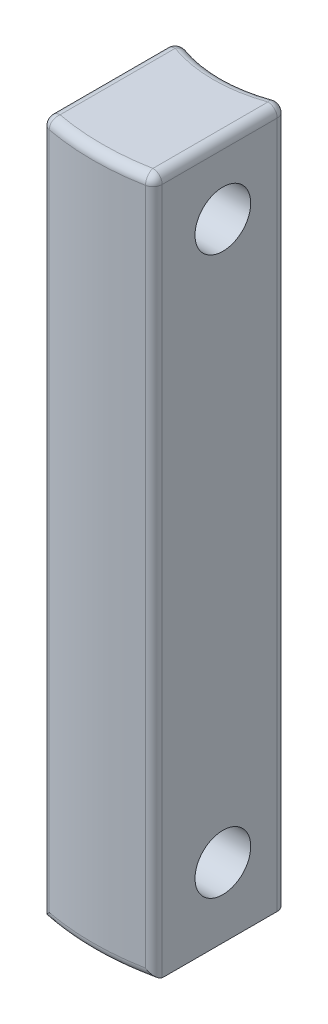
SolidWorks part; units mm, degrees
ref_plane "Front Plane" through (0, 0, 0) normal (0, 0, 1) x (1, 0, 0)
ref_plane "Top Plane" through (0, 0, 0) normal (0, 1, 0) x (1, 0, 0)
ref_plane "Right Plane" through (0, 0, 0) normal (1, 0, 0) x (0, 0, -1)
sketch "Sketch1" plane through (0, 0, 0) normal (0, 1, 0) x (1, 0, 0)
  line L0 (-43.9019, 0) -> (64.6333, 0) construction
  line L1 (0, 40.3951) -> (0, -24.5761) construction
  line L2 (-6, 7.3502) -> (-6, -7.3502)
  line L3 (6, 7.3502) -> (6, -7.3502)
  arc A0 (-6, 7.3502) -> (6, 7.3502) centre (0, 19.9993) ccw
  arc A1 (-6, -7.3502) -> (6, -7.3502) centre (0, 19.9993) ccw
  point P10 (0, 0)
  point P12 (-6.0721, -7.8093)
  point P13 (0, 5.9993)
  point P14 (0, -8.0007)
  point P15 (6, 6.9847)
  point P16 (6, 10.4358)
  point P17 (0, 0)
  dimension "D1" = 14
  dimension "D3" = 28
  dimension "D2" = 12
  dimension "D4" = 14
extrude "Boss-Extrude1" add sketch "Sketch1" along normal mid plane 75
sketch "Sketch2" plane through (0, 0, 0) normal (1, 0, 0) x (0, 0, -1)
  line L0 (-20.8506, 0) -> (32.7315, 0) construction
  line L1 (0, 36.8377) -> (0, -45.48) construction
  circle A0 centre (0, 30) radius 3
  circle A1 centre (0, -30) radius 3
  point P9 (0, 36.8377)
  point P10 (0, -45.48)
  point P11 (0, 0)
  dimension "D2" = 6
  dimension "D1" = 60
extrude "Cut-Extrude1" cut sketch "Sketch2" against normal through all both and the other way through all contours A0 | A1
fillet "Fillet1" radius 1 10 edges at (6, 0, -7.3502) (-6, 0, -7.3502) (0, -37.5, -5.9993) (-6, 0, 7.3502) (6, 0, 7.3502) (0, -37.5, 8.0007) (6, 37.5, 0) (0, 37.5, 8.0007) (-6, 37.5, 0) (0, 37.5, -5.9993)
